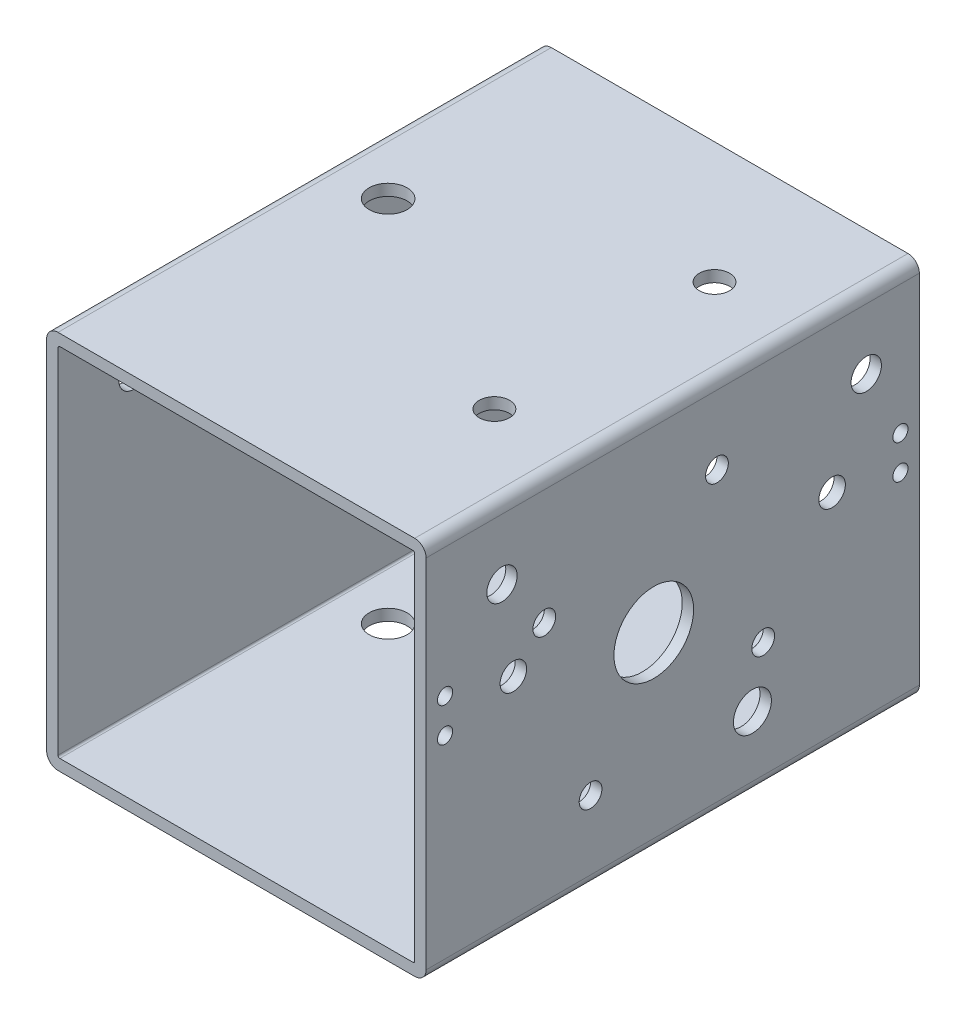
SolidWorks part; units mm, degrees
ref_plane "Front Plane" through (0, 0, 0) normal (0, 0, 1) x (1, 0, 0)
ref_plane "Top Plane" through (0, 0, 0) normal (0, 1, 0) x (1, 0, 0)
ref_plane "Right Plane" through (0, 0, 0) normal (1, 0, 0) x (0, 0, -1)
sketch "Sketch1" plane through (0, 0, 0) normal (0, 0, 1) x (1, 0, 0)
  line L1 (-50, 50) -> (50, 50)
  line L2 (-50, 50) -> (-50, -50)
  line L3 (-50, -50) -> (50, -50)
  line L4 (50, 50) -> (50, -50)
  line L5 (-50, 50) -> (50, -50) construction
  line L6 (-50, -50) -> (50, 50) construction
  point P0 (0, 0)
  dimension "D1" = 100
  dimension "D2" = 100
extrude "Extrude-Thin1" add sketch "Sketch1" along normal blind 130 thin
fillet "Fillet1" radius 0.5 4 edges at (-47, -47, 65) (-47, 47, 65) (47, 47, 65) (47, -47, 65)
fillet "Fillet2" radius 3 4 edges at (50, -50, 65) (-50, -50, 65) (50, 50, 65) (-50, 50, 65)
sketch "Holes - top" plane through (0, 0, 0) normal (0, 1, 0) x (1, 0, 0)
  line L0 (-3, 0) -> (-3, -130) construction
  line L1 (47, -130) -> (-47, -130) construction
  line L2 (-23, 0) -> (-23, -130) construction
  line L3 (47, 0) -> (-47, 0) construction
  line L4 (17, 0) -> (17, -130) construction
  circle A0 centre (-34, -56) radius 11 construction
  circle A1 centre (28, -90) radius 11 construction
  circle A2 centre (28, -32) radius 11 construction
  dimension "D4" = 22
  dimension "D1" = 40
  dimension "D2" = 40
  dimension "D3" = 32
  dimension "D5" = 56
  dimension "D6" = 3
hole_wizard "Ø8.0 (8) Diameter Hole2" positions "Sketch6" profile "Sketch5" hole size "Ø8.0" standard "ANSI Metric" end condition through all
sketch "Sketch6" plane through (0, 50, 0) normal (0, 1, 0) x (1, 0, 0)
  point P0 (28, -32)
  point P6 (28, -90)
sketch "Sketch5" plane through (28, 50, 32) normal (1, 0, 0) x (0, 0, 1)
  line L0 (0, 0) -> (0, 100)
  line L1 (0, 100) -> (4, 100)
  line L2 (4, 100) -> (4, 0)
  line L5 (4, 0) -> (0, 0)
  line L11 (0, -6.35) -> (0, 107.95) construction
  dimension "Thru Hole Dia." = 8
  dimension "Thru Hole Depth" = 100
sketch "Holes - side" plane through (0, 0, 0) normal (1, 0, 0) x (0, 0, -1)
  line L0 (0, 0) -> (-130, 0) construction
  line L1 (-130, -47) -> (-130, 47) construction
  line L2 (-130, 20) -> (0, 20) construction
  line L3 (0, -47) -> (0, 47) construction
  line L4 (-130, -20) -> (0, -20) construction
  circle A0 centre (-110, 31) radius 11 construction
  circle A1 centre (-14, 31) radius 11 construction
  circle A2 centre (-44, -31) radius 11 construction
  dimension "D1" = 40
  dimension "D2" = 22
  dimension "D3" = 20
  dimension "D4" = 14
  dimension "D5" = 44
hole_wizard "Ø8.0 (8) Diameter Hole3" positions "Sketch9" profile "Sketch8" hole size "Ø8.0" standard "ANSI Metric" end condition through all
sketch "Sketch9" plane through (50, 0, 0) normal (1, 0, 0) x (0, 0, -1)
  point P0 (-14, 31)
  point P3 (-110, 31)
sketch "Sketch8" plane through (50, 31, 14) normal (0, 1, 0) x (0, 0, -1)
  line L0 (0, 0) -> (0, 100)
  line L1 (0, 100) -> (4, 100)
  line L2 (4, 100) -> (4, 0)
  line L5 (4, 0) -> (0, 0)
  line L11 (0, -6.35) -> (0, 107.95) construction
  dimension "Thru Hole Dia." = 8
  dimension "Thru Hole Depth" = 100
hole_wizard "Ø10.0 (10) Diameter Hole1" positions "Sketch12" profile "Sketch11" hole size "Ø10.0" standard "ANSI Metric" end condition through all
sketch "Sketch12" plane through (0, 50, 0) normal (0, 1, 0) x (1, 0, 0)
  point P0 (-34, -56)
sketch "Sketch11" plane through (-34, 50, 56) normal (1, 0, 0) x (0, 0, 1)
  line L0 (0, 0) -> (0, 100)
  line L1 (0, 100) -> (5, 100)
  line L2 (5, 100) -> (5, 0)
  line L5 (5, 0) -> (0, 0)
  line L11 (0, -6.35) -> (0, 107.95) construction
  dimension "Thru Hole Dia." = 10
  dimension "Thru Hole Depth" = 100
hole_wizard "Ø10.0 (10) Diameter Hole2" positions "Sketch14" profile "Sketch13" hole size "Ø10.0" standard "ANSI Metric" end condition through all
sketch "Sketch14" plane through (50, 0, 0) normal (1, 0, 0) x (0, 0, -1)
  point P0 (-44, -31)
sketch "Sketch13" plane through (50, -31, 44) normal (0, 1, 0) x (0, 0, -1)
  line L0 (0, 0) -> (0, 100)
  line L1 (0, 100) -> (5, 100)
  line L2 (5, 100) -> (5, 0)
  line L5 (5, 0) -> (0, 0)
  line L11 (0, -6.35) -> (0, 107.95) construction
  dimension "Thru Hole Dia." = 10
  dimension "Thru Hole Depth" = 100
hole_wizard "M8x1.25 Tapped Hole1" positions "Sketch18" profile "Sketch17" tap size "M8x1.25" standard "ANSI Metric"
sketch "Sketch18" plane through (-50, 0, 0) normal (-1, 0, 0) x (0, 0, 1)
  line L0 (56, 35) -> (56, -15) construction
  point P0 (56, -15)
  point P2 (56, 35)
  dimension "D1" = 56
  dimension "D2" = 35
  dimension "D3" = 15
sketch "Sketch17" plane through (-50, -15, 56) normal (0, 1, 0) x (0, 0, 1)
  line L0 (0, 0) -> (0, 3)
  line L1 (0, 3) -> (3.4, 3)
  line L2 (3.4, 3) -> (3.4, 0)
  line L5 (3.4, 0) -> (0, 0)
  line L11 (0, -6.35) -> (0, 107.95) construction
  dimension "Thru Tap Drill Dia." = 6.8
  dimension "Thru Tap Drill Depth" = 3
cosmetic thread "Hole Thread1" parameters "D2"=8
cosmetic thread "Hole Thread2" parameters "D2"=8
hole_wizard "M8x1.25 Tapped Hole2" positions "Sketch21" profile "Sketch20" tap size "M8x1.25" standard "ANSI Metric"
sketch "Sketch21" plane through (0, -50, 0) normal (0, -1, 0) x (-1, 0, 0)
  line L0 (20, -44) -> (-35, -44) construction
  point P0 (20, -44)
  point P2 (-35, -44)
  dimension "D1" = 44
  dimension "D2" = 35
  dimension "D3" = 20
sketch "Sketch20" plane through (-20, -50, 44) normal (1, 0, 0) x (0, 0, -1)
  line L0 (0, 0) -> (0, 3)
  line L1 (0, 3) -> (3.4, 3)
  line L2 (3.4, 3) -> (3.4, 0)
  line L5 (3.4, 0) -> (0, 0)
  line L11 (0, -6.35) -> (0, 107.95) construction
  dimension "Thru Tap Drill Dia." = 6.8
  dimension "Thru Tap Drill Depth" = 3
cosmetic thread "Hole Thread3" parameters "D2"=8
cosmetic thread "Hole Thread4" parameters "D2"=8
sketch "Holes - Nema 23 motor" plane through (0, 0, 0) normal (1, 0, 0) x (0, 0, -1)
  line L0 (-98.8427, 16.6524) -> (-53.3476, 28.8427) construction
  line L1 (-98.8427, 16.6524) -> (-86.6524, -28.8427) construction
  line L2 (-53.3476, 28.8427) -> (-41.1573, -16.6524) construction
  line L3 (-86.6524, -28.8427) -> (-41.1573, -16.6524) construction
  line L4 (-98.8427, 16.6524) -> (-41.1573, -16.6524) construction
  line L5 (-53.3476, 28.8427) -> (-86.6524, -28.8427) construction
  line L6 (0, 0) -> (-130, 0) construction
  point P1 (-70, 0)
  dimension "D1" = 70
  dimension "D2" = 47.1
  dimension "D3" = 47.1
  dimension "D4" = 15
hole_wizard "Ø21.0 (21) Diameter Hole1" positions "Sketch24" profile "Sketch23" hole size "Ø21.0" standard "ANSI Metric"
sketch "Sketch24" plane through (50, 0, 0) normal (1, 0, 0) x (0, 0, -1)
  point P0 (-70, 0)
sketch "Sketch23" plane through (50, 0, 70) normal (0, 1, 0) x (0, 0, -1)
  line L0 (0, 0) -> (0, 3)
  line L1 (0, 3) -> (10.5, 3)
  line L2 (10.5, 3) -> (10.5, 0)
  line L5 (10.5, 0) -> (0, 0)
  line L11 (0, -6.35) -> (0, 107.95) construction
  dimension "Thru Hole Dia." = 21
  dimension "Thru Hole Depth" = 3
hole_wizard "Ø6.0 (6) Diameter Hole1" positions "Sketch26" profile "Sketch25" hole size "Ø6.0" standard "ANSI Metric"
sketch "Sketch26" plane through (50, 0, 0) normal (1, 0, 0) x (0, 0, -1)
  point P0 (-41.1573, -16.6524)
  point P3 (-53.3476, 28.8427)
  point P6 (-98.8427, 16.6524)
  point P9 (-86.6524, -28.8427)
sketch "Sketch25" plane through (50, -16.6524, 41.1573) normal (0, 1, 0) x (0, 0, -1)
  line L0 (0, 0) -> (0, 3)
  line L1 (0, 3) -> (3, 3)
  line L2 (3, 3) -> (3, 0)
  line L5 (3, 0) -> (0, 0)
  line L11 (0, -6.35) -> (0, 107.95) construction
  dimension "Thru Hole Dia." = 6
  dimension "Thru Hole Depth" = 3
sketch "Sketch27" plane through (50, 0, 0) normal (1, 0, 0) x (0, 0, -1)
  line L1 (0, -47) -> (0, 47) construction
  line L2 (-130, 50) -> (0, 50) construction
  line L3 (-65, 66.9997) -> (-65, -40.3101) construction
  line L4 (-130, -47) -> (-130, 47) construction
  circle A0 centre (-5, 13) radius 2
  circle A1 centre (-5, 4) radius 2
  circle A2 centre (-23, 8.5) radius 3.5
  circle A3 centre (-107, 8.5) radius 3.5
  circle A4 centre (-125, 4) radius 2
  circle A5 centre (-125, 13) radius 2
  dimension "D1" = 4
  dimension "D2" = 9
  dimension "D3" = 5
  dimension "D4" = 46
  dimension "D7" = 18
  dimension "D8" = 4.5
  dimension "D9" = 7
  dimension "D5" = 0
  dimension "D6" = 65
extrude "Cut-Extrude1" cut sketch "Sketch27" against normal up to next
equation "\"a\"= \"Trolley Profile@Plasma Beta.Assembly\""
equation "\"b\"= \"Trolley Profile Thickness@Plasma Beta.Assembly\""
equation "\"L\"= 130"
equation "\"D2@Sketch1\"=\"a\""
equation "\"D1@Sketch1\"=\"a\""
equation "\"D1@Extrude-Thin1\"=\"L\""
equation "\"D5@Extrude-Thin1\"=\"b\""
equation "\"D1@Fillet2\"=\"b\""
equation "\"d-bearing\"= 22'diameter of bearing"
equation "\"a-small\"= \"Beam Profile@Plasma Beta.Assembly\"'profile of smaller beam"
equation "\"D4@Holes - top\"=\"d-bearing\""
equation "\"D2@Holes - side\"=\"d-bearing\""
equation "\"D1@Holes - top\"=\"a-small\""
equation "\"D1@Holes - side\"=\"a-small\""
